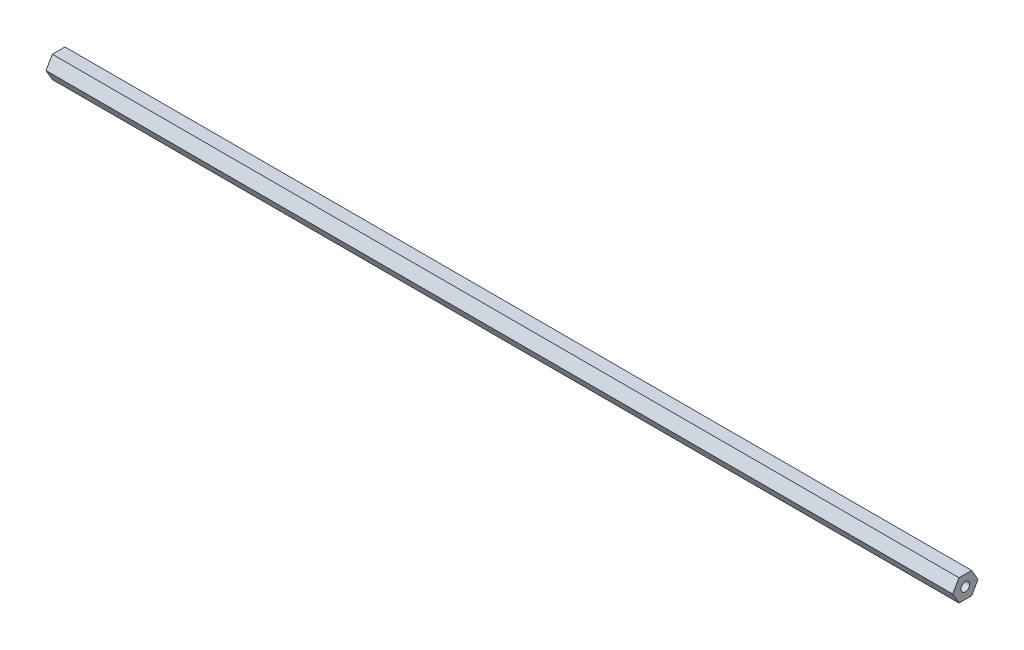
SolidWorks part; units mm, degrees
material "Plain Carbon Steel"
ref_plane "Front Plane" through (0, 0, 0) normal (0, 0, 1) x (1, 0, 0)
ref_plane "Top Plane" through (0, 0, 0) normal (0, 1, 0) x (1, 0, 0)
ref_plane "Right Plane" through (0, 0, 0) normal (1, 0, 0) x (0, 0, -1)
sketch "Sketch1" plane through (0, 0, 0) normal (1, 0, 0) x (0, 0, -1)
  line L1 (7.3323, 0) -> (3.6662, 6.35)
  line L2 (3.6662, 6.35) -> (-3.6662, 6.35)
  line L3 (-3.6662, 6.35) -> (-7.3323, 0)
  line L4 (-7.3323, 0) -> (-3.6662, -6.35)
  line L5 (-3.6662, -6.35) -> (3.6662, -6.35)
  line L6 (3.6662, -6.35) -> (7.3323, 0)
  circle A0 centre (0, 0) radius 6.35 construction
  dimension "D1" = 12.7
extrude "Boss-Extrude1" add sketch "Sketch1" along normal blind 525.4625
hole_wizard "1/4-20 Tapped Hole1" positions "Sketch3" profile "Sketch4" tap size "1/4-20" standard "ANSI Inch"
sketch "Sketch3" plane through (525.4625, 0, 0) normal (1, 0, 0) x (0, 0, -1)
  point P0 (0, 0)
cosmetic thread "Hole Thread1" parameters "D1"=12.7, "D2"=6.35
sketch "Sketch4" plane through (525.4625, 0, 0) normal (0, 1, 0) x (0, 0, -1)
  line L0 (0, 0) -> (0, 18.0438)
  line L1 (0, 18.0438) -> (2.5527, 16.51)
  line L2 (2.5527, 16.51) -> (2.5527, 0)
  line L5 (2.5527, 0) -> (0, 0)
  line L10 (0, 18.0438) -> (-2.5527, 16.51) construction
  line L11 (0, -6.35) -> (0, 107.95) construction
  dimension "Tap Drill Dia." = 5.1054
  dimension "Tap Drill Depth" = 16.51
  dimension "Drill Angle" = 118
hole_wizard "1/4-20 Tapped Hole2" positions "Sketch5" profile "Sketch6" tap size "1/4-20" standard "ANSI Inch"
sketch "Sketch5" plane through (0, 0, 0) normal (-1, 0, 0) x (0, 0, 1)
  point P0 (0, 0)
sketch "Sketch6" plane through (0, 0, 0) normal (0, 1, 0) x (0, 0, 1)
  line L0 (0, 0) -> (0, 18.0438)
  line L1 (0, 18.0438) -> (2.5527, 16.51)
  line L2 (2.5527, 16.51) -> (2.5527, 0)
  line L5 (2.5527, 0) -> (0, 0)
  line L10 (0, 18.0438) -> (-2.5527, 16.51) construction
  line L11 (0, -6.35) -> (0, 107.95) construction
  dimension "Tap Drill Dia." = 5.1054
  dimension "Tap Drill Depth" = 16.51
  dimension "Drill Angle" = 118
cosmetic thread "Hole Thread2" parameters "D1"=12.7, "D2"=6.35
